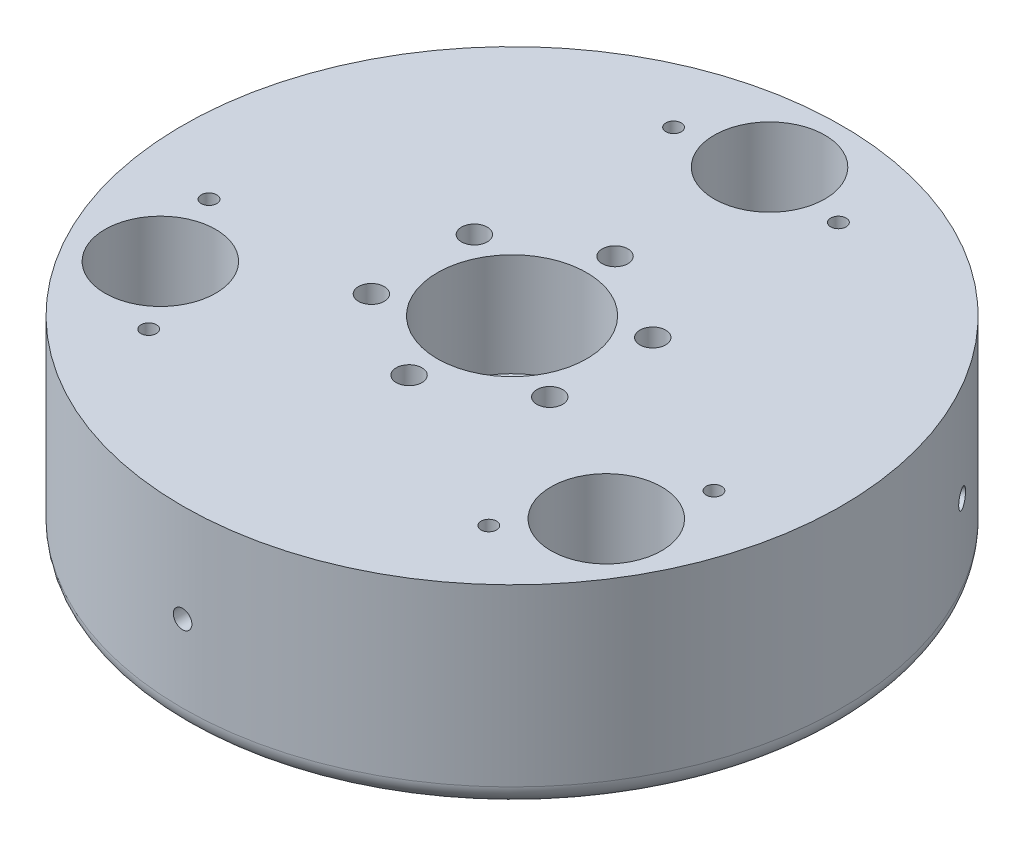
SolidWorks part; units mm, degrees
ref_plane "Спереди" through (0, 0, 0) normal (0, 0, 1) x (1, 0, 0)
ref_plane "Сверху" through (0, 0, 0) normal (0, 1, 0) x (1, 0, 0)
ref_plane "Справа" through (0, 0, 0) normal (1, 0, 0) x (0, 0, -1)
sketch "Эскиз1" plane through (0, 0, 0) normal (0, 1, 0) x (1, 0, 0)
  circle A3 centre (0, 0) radius 32
  circle A4 centre (0, 0) radius 4
  circle A6 centre (0, 0) radius 25 construction
  circle A7 centre (0, 25) radius 3
  circle A8 centre (21.6506, -12.5) radius 3
  circle A9 centre (-21.6506, -12.5) radius 3
  dimension "D4" = 64
  dimension "D1" = 8
  dimension "D2" = 50
  dimension "D3" = 6
  dimension "D5" = 3
extrude "Бобышка-Вытянуть1" add sketch "Эскиз1" along normal blind 19
fillet "Скругление1" radius 2 1 edges at (0, 0, 32)
sketch "Эскиз2" plane through (0, 19, 0) normal (0, 1, 0) x (1, 0, 0)
  circle A0 centre (0, 25) radius 5.375
  circle A2 centre (21.6506, -12.5) radius 5.375
  circle A3 centre (-21.6506, -12.5) radius 5.375
  circle A4 centre (-21.6506, -12.5) radius 3 construction
  dimension "D1" = 10.75
  dimension "D2" = 3
extrude "Вырез-Вытянуть1" cut sketch "Эскиз2" against normal blind 15.5
sketch "Эскиз3" plane through (0, 0, 0) normal (0, -1, 0) x (1, 0, 0)
  circle A0 centre (0, 0) radius 25 construction
  circle A1 centre (0, 25) radius 2.625
  circle A2 centre (21.6506, -12.5) radius 2.625
  circle A3 centre (-21.6506, -12.5) radius 2.625
  dimension "D2" = 3
  dimension "D1" = 5.25
extrude "Вырез-Вытянуть2" cut sketch "Эскиз3" against normal blind 15
sketch "Эскиз4" plane through (0, 19, 0) normal (0, 1, 0) x (1, 0, 0)
  circle A0 centre (0, 0) radius 10 construction
  circle A1 centre (0, 10) radius 1.25
  circle A2 centre (8.6603, 5) radius 1.25
  circle A3 centre (8.6603, -5) radius 1.25
  circle A4 centre (0, -10) radius 1.25
  circle A5 centre (-8.6603, -5) radius 1.25
  circle A6 centre (-8.6603, 5) radius 1.25
  dimension "D3" = 6
  dimension "D1" = 20
  dimension "D2" = 2.5
extrude "Вырез-Вытянуть3" cut sketch "Эскиз4" against normal through all
sketch "Эскиз7" plane through (0, 0, 0) normal (0, -1, 0) x (1, 0, 0)
  circle A0 centre (0, 10) radius 1.95 construction
  circle A7 centre (8.6603, 5) radius 1.95
  circle A8 centre (8.6603, -5) radius 1.95 construction
  circle A9 centre (0, -10) radius 1.95
  circle A10 centre (-8.6603, -5) radius 1.95 construction
  circle A11 centre (-8.6603, 5) radius 1.95
  circle A12 centre (8.6603, 5) radius 1.25 construction
  dimension "D1" = 3.9
  dimension "D2" = 6
extrude "Вырез-Вытянуть5" cut sketch "Эскиз7" against normal offset from surface (3 mm away) 16 up to face at (0, 19, -8.75)
chamfer "Фаска1" distance 1 angle 45 7 edges at (21.6506, 0, -15.125) (0, 0, -22) (-21.6506, 0, -15.125) (-21.6506, 0, 15.5) (0, 0, 22.375) (21.6506, 0, 15.5) (0, 0, 4)
sketch "Эскиз8" plane through (0, 19, 0) normal (0, 1, 0) x (1, 0, 0)
  circle A0 centre (0, 0) radius 7.25
  dimension "D1" = 14.5
extrude "Вырез-Вытянуть6" cut sketch "Эскиз8" against normal blind 10
sketch "Эскиз9" plane through (0, 19, 0) normal (0, 1, 0) x (1, 0, 0)
  line L0 (0, 0) -> (0, 25) construction
  line L1 (-8, 23.6854) -> (8, 23.6854) construction
  circle A0 centre (0, 0) radius 25 construction
  circle A1 centre (-8, 23.6854) radius 0.75
  circle A2 centre (8, 23.6854) radius 0.75
  circle A3 centre (16.5122, -18.7709) radius 0.75
  circle A4 centre (24.5122, -4.9145) radius 0.75
  circle A5 centre (-24.5122, -4.9145) radius 0.75
  circle A6 centre (-16.5122, -18.7709) radius 0.75
  dimension "D1" = 16
  dimension "D2" = 1.5
  dimension "D3" = 1.5
  dimension "D4" = 3
extrude "Вырез-Вытянуть7" cut sketch "Эскиз9" against normal through all
ref_plane "Плоскость1" through (0, 0, 32) normal (0, 0, 1) x (1, 0, 0)
sketch "Эскиз11" plane through (0, 0, 32) normal (0, 0, 1) x (1, 0, 0)
  line L0 (0, 0) -> (0, 19) construction
  line L1 (-30, 0) -> (30, 0) construction
  line L2 (1.25, 19) -> (-1.25, 19) construction
  circle A0 centre (0, 9.5) radius 0.9
  dimension "D1" = 1.8
extrude "Вырез-Вытянуть9" cut sketch "Эскиз11" against normal up to next
pattern_circular "Круговой массив7" count 3 over 360 about axis through (0, 19, 0) along (0, -1, 0) of "Вырез-Вытянуть9"
equation "\"motor_diameter\"= 30"
equation "\"mm_diameter\"= IIF ( \"motor_diameter\" < 34 , 41 , \"motor_diameter\" + 8 )"
equation "\"upper_shafts_diameter\"= 5"
equation "\"upper_shats_length\"= 180"
equation "\"upper_bearing_d1\"= 10"
equation "\"upper_bearing_d2\"= 5"
equation "\"upper_bearing_h\"= 15"
equation "\"lower_shafts_diameter\"= 5"
equation "\"lower_shafts_length\"= 180"
equation "\"lower_bearing_d1\"= 10"
equation "\"lower_bearing_d2\"= 5"
equation "\"lower_bearing_h\"= 15"
equation "\"print_offset\"= 0.5"
equation "\"bh_screws_d\"= 2"
equation "\"bh_screws_h\"= 20"
equation "\"bh_screws_hh_d\"= 3.4"
equation "\"bh_screws_hh_h\"= 2"
equation "\"bh_nut_d\"= 3.8"
equation "\"bh_nut_h\"= 2"
equation "\"motor_screws_d\"= 3"
equation "\"motor_screws_h\"= 16"
equation "\"motor_screws_hh_d\"= 5.5"
equation "\"motor_screws_hh_h\"= 3"
equation "\"plate_hole_distance\"= 25.4"
equation "\"plate_screws_d\"= 6.5"
equation "\"shafts_diameter\"= IIF ( \"mm_diameter\" < 42 , 42 + 8 , \"mm_diameter\" + 8 )"
equation "\"D4@Эскиз1\"= \"system_radius\" * 2"
equation "\"central_hole_diameter\"= 8"
equation "\"bh_thikness\"= 4"
equation "\"D1@Эскиз1\"=\"central_hole_diameter\""
equation "\"D2@Эскиз1\"=\"shafts_diameter\""
equation "\"D3@Эскиз1\" = \"lower_shafts_diameter\" + 1"
equation "\"D1@Бобышка-Вытянуть1\" = \"bh_thikness\" + \"lower_bearing_h\""
equation "\"D1@Эскиз2\" = \"lower_bearing_d1\" + \"print_offset\" * 1.5"
equation "\"D1@Вырез-Вытянуть1\" = \"lower_bearing_h\" + \"print_offset\""
equation "\"D1@Эскиз3\" = \"upper_shafts_diameter\" + \"print_offset\" / 2"
equation "\"D1@Вырез-Вытянуть2\"= \"upper_bearing_h\""
equation "\"D2@Эскиз4\"=\"bh_screws_d\"+\"print_offset\""
equation "\"D1@Вырез-Вытянуть5\"=\"bh_screws_h\"-\"bh_thikness\""
equation "\"D1@Эскиз7\"=\"bh_screws_hh_d\"+\"print_offset\""
equation "\"D1@Вырез-Вытянуть6\"=14-\"bh_thikness\""
equation "\"D2@Эскиз9\"=\"bh_screws_d\"-\"print_offset\""
equation "\"D3@Эскиз9\"=\"D2@Эскиз9\""
equation "\"ends_screws_d\"= 4"
equation "\"ends_screws_h\"= 16"
equation "\"ends_screws_hh_d\"= 6.7"
equation "\"ends_screws_hh_h\"= 4.1"
equation "\"ends_nut_d\"= 6.8"
equation "\"ends_nut_h\"= 3"
equation "\"system_radius\" = ( \"shafts_diameter\" + 12 + \"bh_thikness\" / 2 ) / 2"
equation "\"encoder_distance\"= \"system_radius\" + 4"
equation "\"tape_position\"= \"encoder_distance\" - 2 + 3.9 + 1.7 / 2"
equation "\"ft_sensor_d1\" = 9.8"
equation "\"ft_sensor_d2\"= 24.9"
equation "\"ft_sensor_h\"= 7"
equation "\"carbon_pipe_d\"= 14"
equation "\"D1@Эскиз8\"=\"print_offset\"+14.00мм"
equation "\"D1@Эскиз11\"=\"bh_screws_d\"-0.2"
